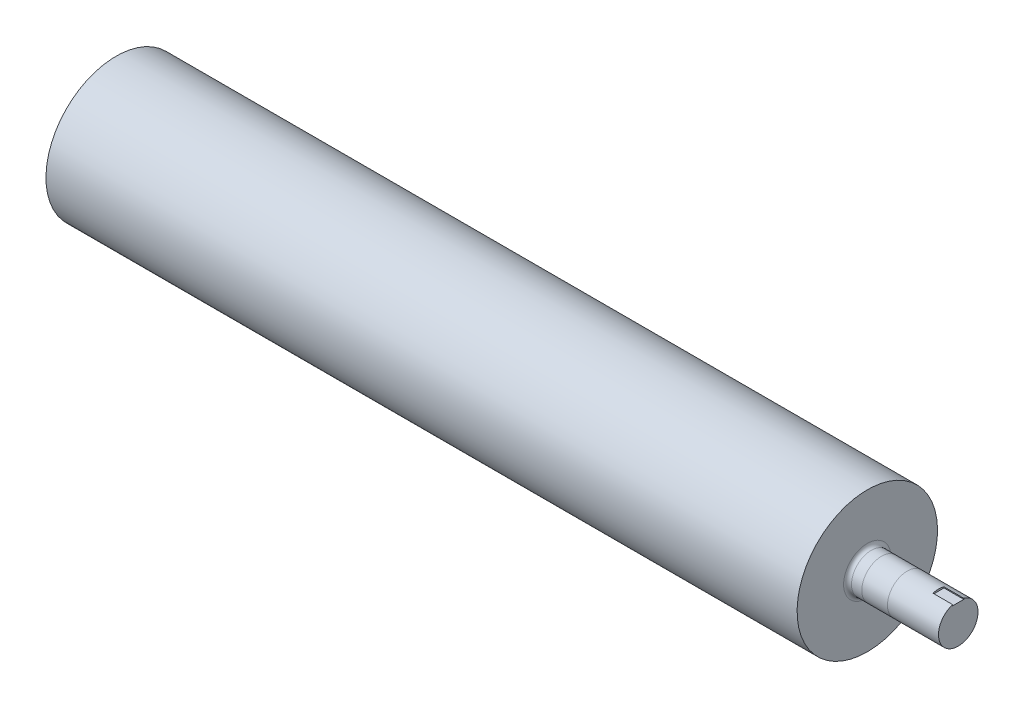
SolidWorks part; units mm, degrees
ref_plane "Front Plane" through (0, 0, 0) normal (0, 0, 1) x (1, 0, 0)
ref_plane "Top Plane" through (0, 0, 0) normal (0, 1, 0) x (1, 0, 0)
ref_plane "Right Plane" through (0, 0, 0) normal (1, 0, 0) x (0, 0, -1)
sketch "Sketch1" plane through (0, 0, 0) normal (0, 0, 1) x (1, 0, 0)
  line L0 (0, 0) -> (0, -158504.3026) construction
  line L1 (-1040, 0) -> (1180, 0)
  line L2 (-1040, 0) -> (-1040, 50)
  line L3 (-1040, 50) -> (-950, 50)
  line L4 (-950, 50) -> (-950, 177.5957)
  line L6 (950, 177.5957) -> (950, 50)
  line L7 (950, 50) -> (1180, 50)
  line L8 (1180, 50) -> (1180, 0)
  line L9 (-950, 177.5957) -> (0, 177.5957)
  line L10 (0, 177.5957) -> (950, 177.5957)
  dimension "D1" = 50
  dimension "D2" = 950
  dimension "D3" = 90
  dimension "D4" = 230
  dimension "D5" = 50
  dimension "D6" = 950
revolve "Revolve1" add sketch "Sketch1" angle 360 about L1
fillet "Fillet1" radius 10 2 edges at (-950, -50, 0) (950, -50, 0)
sketch "Sketch2" plane through (1180, 0, 0) normal (1, 0, 0) x (0, 0, -1)
  line L0 (0, 0) -> (0, -50000) construction
  line L1 (-14, 48) -> (14, 48) construction
  line L2 (-14, 50.6) -> (14, 50.6)
  line L3 (-14, 50.6) -> (-14, 45.4)
  line L4 (-14, 45.4) -> (14, 45.4)
  line L5 (14, 50.6) -> (14, 45.4)
  line L6 (-14, 50.6) -> (14, 45.4) construction
  line L7 (-14, 45.4) -> (14, 50.6) construction
  circle A1 centre (0, 0) radius 50
  circle A2 centre (0, 0) radius 50
  point P0 (0, 48)
  point P12 (0, 0)
  circle M7 centre (0, 0) radius 50
  dimension "D2" = 28
  dimension "D3" = 2.6
  dimension "D1" = 0
extrude "Cut-Extrude1" cut sketch "Sketch2" against normal blind 50 contours L5 L3 L4 M7
sketch "Sketch3" plane through (0, 0, 0) normal (0, 0, 1) x (1, 0, 0)
  line L0 (-975, 272.8318) -> (-975, -376.9833)
  line L1 (986, 293.2093) -> (986, -343.0209)
  line L2 (1051, 272.8318) -> (1051, -358.87)
  line L3 (1180, -50) -> (1180, 48) construction
  line L4 (-1040, 50) -> (-1040, -50) construction
  point P10 (986, 293.2093)
  point P11 (1051, -358.87)
  dimension "D1" = 129
  dimension "D2" = 65
  dimension "D3" = 65
split line "Split Line1"
